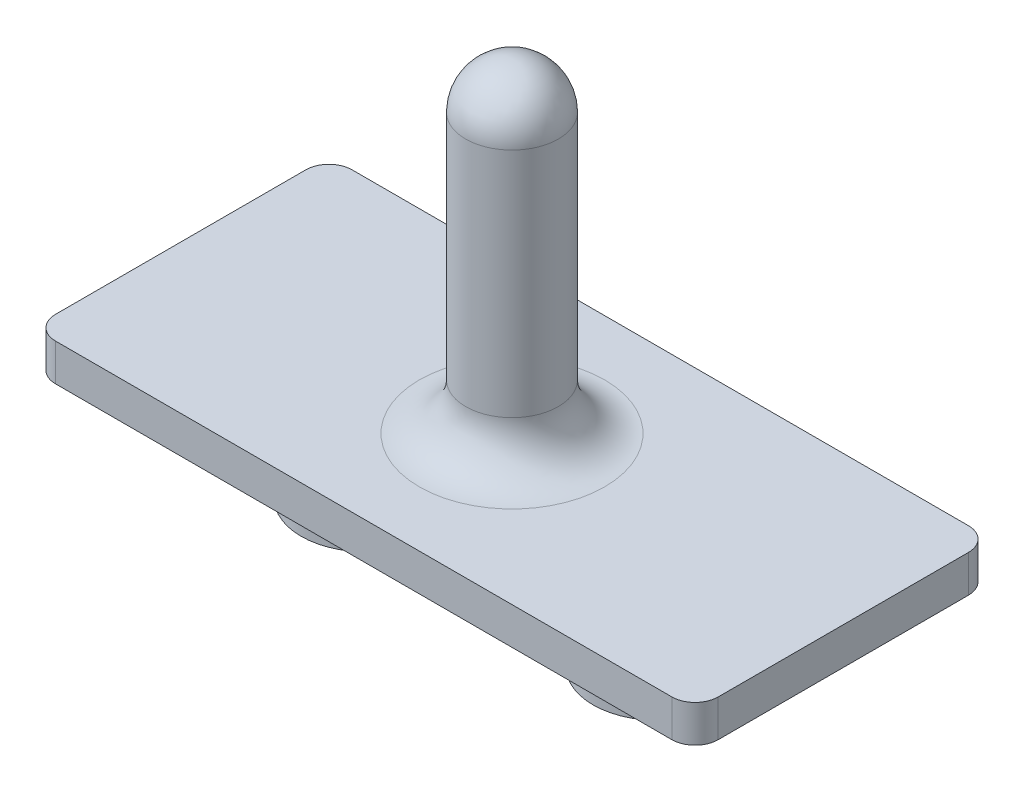
SolidWorks part; units mm, degrees
ref_plane "Front Plane" through (0, 0, 0) normal (0, 0, 1) x (1, 0, 0)
ref_plane "Top Plane" through (0, 0, 0) normal (0, 1, 0) x (1, 0, 0)
ref_plane "Right Plane" through (0, 0, 0) normal (1, 0, 0) x (0, 0, -1)
sketch "Sketch1" plane through (0, 0, 0) normal (0, 1, 0) x (1, 0, 0)
  line L1 (0, 0) -> (36.322, 0)
  line L2 (0, 0) -> (0, -16.256)
  line L3 (0, -16.256) -> (36.322, -16.256)
  line L4 (36.322, 0) -> (36.322, -16.256)
  dimension "D1" = 16.256
  dimension "D2" = 36.322
extrude "Boss-Extrude1" add sketch "Sketch1" along normal blind 2.032
sketch "Sketch2" plane through (0, 2.032, 0) normal (0, 1, 0) x (1, 0, 0)
  line L0 (0, 0) -> (0, -16.256) construction
  line L2 (0, -16.256) -> (36.322, -16.256) construction
  circle A0 centre (18.161, -8.128) radius 2.54
  dimension "D1" = 18.161
  dimension "D3" = 5.08
  dimension "D2" = 8.128
extrude "Boss-Extrude2" add sketch "Sketch2" along normal blind 17.78
fillet "Fillet1" radius 2.54 1 edges at (18.161, 19.812, 10.668)
fillet "Fillet2" radius 2.54 1 edges at (18.161, 2.032, 10.668)
fillet "Fillet3" radius 1.27 4 edges at (36.322, 1.016, 0) (36.322, 1.016, 16.256) (0, 1.016, 0) (0, 1.016, 16.256)
sketch "Sketch3" plane through (0, 0, 0) normal (0, -1, 0) x (1, 0, 0)
  line L0 (1.27, 16.256) -> (35.052, 16.256) construction
  line L1 (0, 1.27) -> (0, 14.986) construction
  line L2 (36.322, 14.986) -> (36.322, 1.27) construction
  circle A0 centre (10.16, 8.128) radius 3.556
  circle A1 centre (26.162, 8.128) radius 3.556
  dimension "D1" = 7.112
  dimension "D4" = 7.112
  dimension "D2" = 8.128
  dimension "D3" = 10.16
  dimension "D5" = 8.128
  dimension "D6" = 10.16
extrude "Boss-Extrude3" add sketch "Sketch3" along normal blind 5.08
